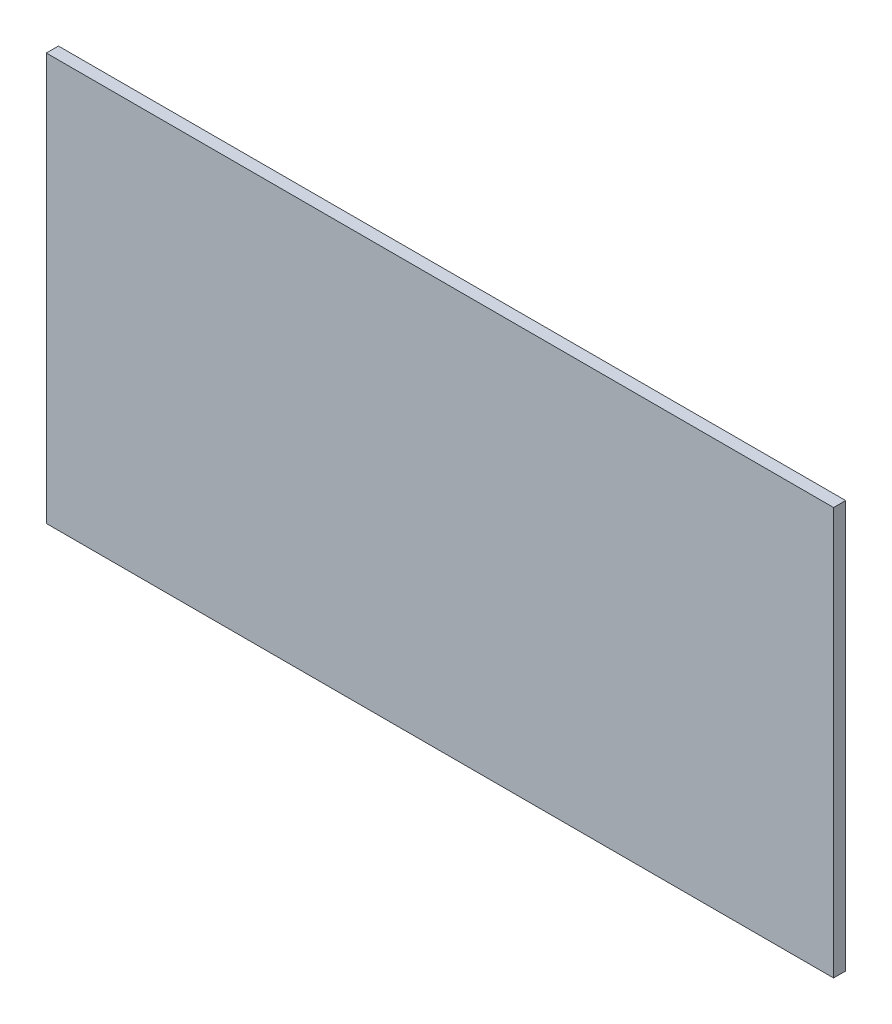
SolidWorks part; units mm, degrees
ref_plane "Front Plane" through (0, 0, 0) normal (0, 0, 1) x (1, 0, 0)
ref_plane "Top Plane" through (0, 0, 0) normal (0, 1, 0) x (1, 0, 0)
ref_plane "Right Plane" through (0, 0, 0) normal (1, 0, 0) x (0, 0, -1)
sketch "Sketch1" plane through (0, 0, 0) normal (0, 0, 1) x (1, 0, 0)
  line L1 (-65, 33.64) -> (65, 33.64)
  line L2 (-65, 33.64) -> (-65, -33.64)
  line L3 (-65, -33.64) -> (65, -33.64)
  line L4 (65, 33.64) -> (65, -33.64)
  line L5 (-65, 33.64) -> (65, -33.64) construction
  line L6 (-65, -33.64) -> (65, 33.64) construction
  point P0 (0, 0)
  dimension "D1" = 67.28
  dimension "D2" = 130
extrude "Boss-Extrude1" add sketch "Sketch1" along normal blind 2
